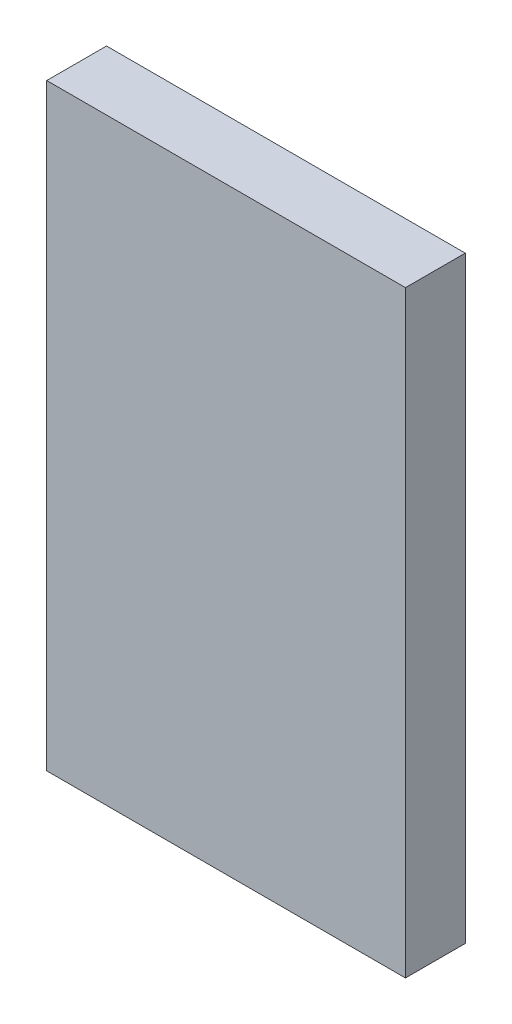
SolidWorks part; units mm, degrees
ref_plane "Plan de face" through (0, 0, 0) normal (0, 0, 1) x (1, 0, 0)
ref_plane "Plan de dessus" through (0, 0, 0) normal (0, 1, 0) x (1, 0, 0)
ref_plane "Plan de droite" through (0, 0, 0) normal (1, 0, 0) x (0, 0, -1)
sketch "Esquisse1" plane through (0, 0, 0) normal (0, 0, 1) x (1, 0, 0)
  line L1 (-19.05, 31.75) -> (19.05, 31.75)
  line L2 (-19.05, 31.75) -> (-19.05, -31.75)
  line L3 (-19.05, -31.75) -> (19.05, -31.75)
  line L4 (19.05, 31.75) -> (19.05, -31.75)
  point P4 (-19.05, 0)
  point P6 (0, -31.75)
  dimension "D1" = 31.75
  dimension "D2" = 38.1
extrude "Boss.-Extru.1" add sketch "Esquisse1" along normal mid plane 6.35
